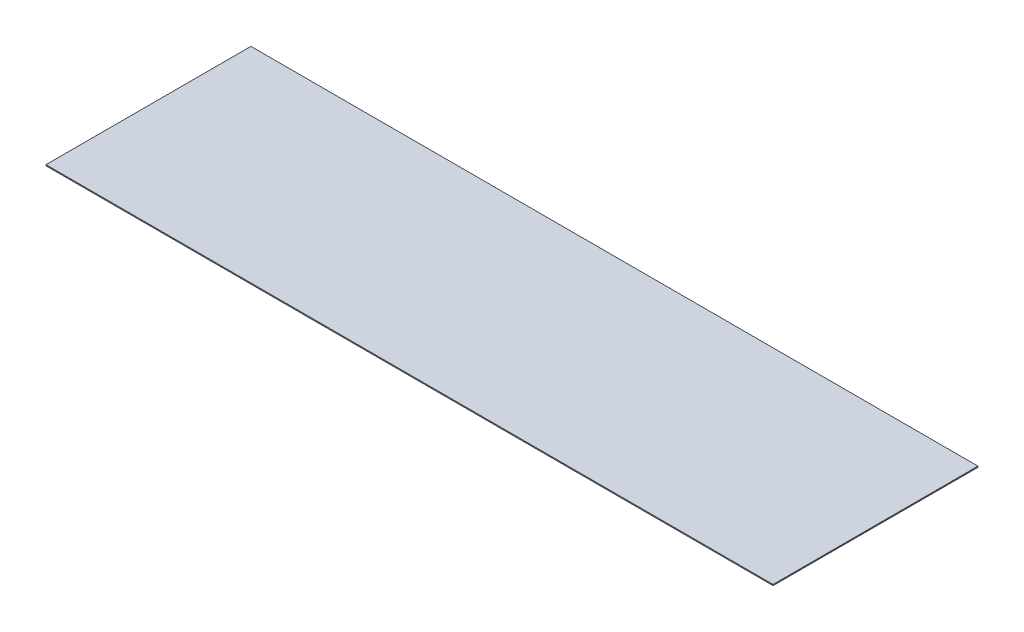
SolidWorks part; units mm, degrees
ref_plane "Front Plane" through (0, 0, 0) normal (0, 0, 1) x (1, 0, 0)
ref_plane "Top Plane" through (0, 0, 0) normal (0, 1, 0) x (1, 0, 0)
ref_plane "Right Plane" through (0, 0, 0) normal (1, 0, 0) x (0, 0, -1)
sketch "Sketch1" plane through (0, 0, 0) normal (0, 1, 0) x (1, 0, 0)
  line L1 (0, 0) -> (1100, 0)
  line L2 (0, 0) -> (0, 310)
  line L3 (0, 310) -> (1100, 310)
  line L4 (1100, 0) -> (1100, 310)
  dimension "D1" = 310
  dimension "D2" = 1100
extrude "Boss-Extrude1" add sketch "Sketch1" along normal blind 1.5875
